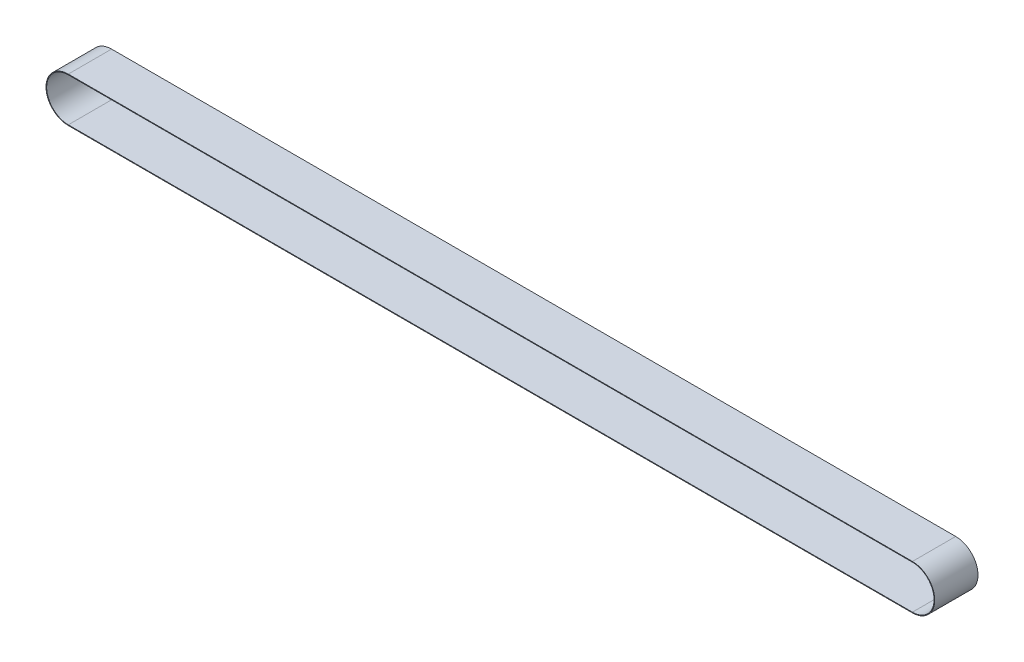
SolidWorks part; units mm, degrees
ref_plane "Ebene vorne" through (0, 0, 0) normal (0, 0, 1) x (1, 0, 0)
ref_plane "Ebene oben" through (0, 0, 0) normal (0, 1, 0) x (1, 0, 0)
ref_plane "Ebene rechts" through (0, 0, 0) normal (1, 0, 0) x (0, 0, -1)
sketch "Skizze2" plane through (0, 0, 0) normal (0, 0, 1) x (1, 0, 0)
  line L0 (0, 0) -> (1, 0) construction
  line L1 (0, 0) -> (0, 1) construction
  line L2 (0, 100) -> (3900, 100)
  line L3 (3900, -100) -> (0, -100)
  arc A0 (0, -100) -> (0, 100) centre (0, 0) cw
  arc A1 (3900, 100) -> (3900, -100) centre (3900, 0) cw
extrude "Linear-Austragen-Dünn1" add sketch "Skizze2" along normal mid plane 200 thin thin type one direction wall 3
